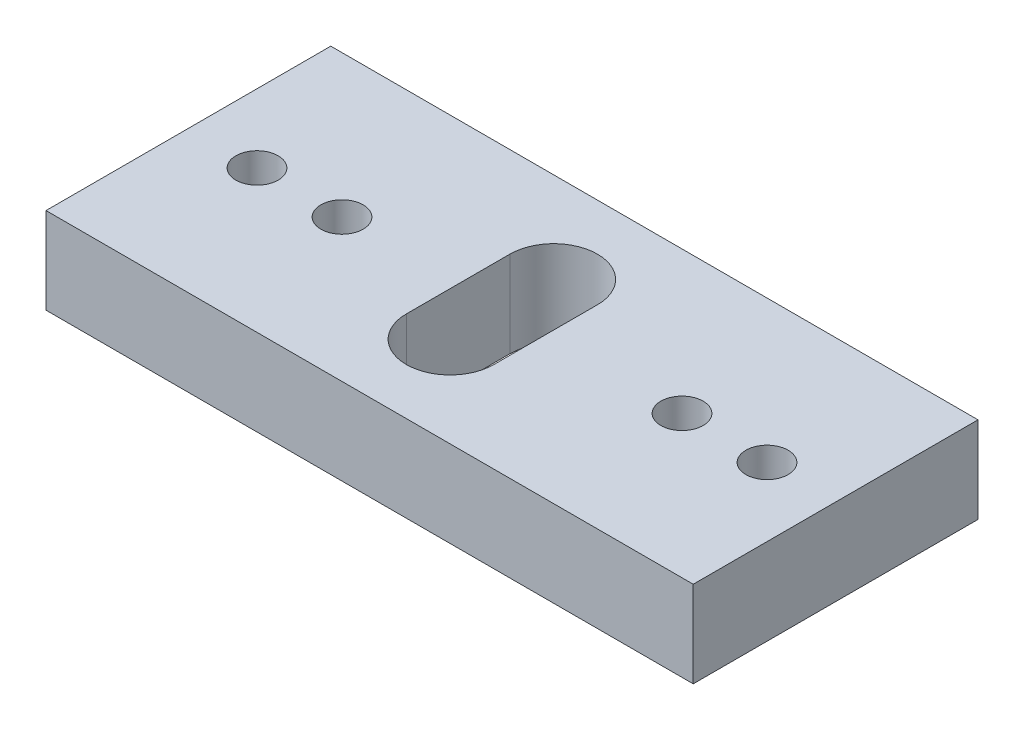
SolidWorks part; units mm, degrees
ref_plane "Front Plane" through (0, 0, 0) normal (0, 0, 1) x (1, 0, 0)
ref_plane "Top Plane" through (0, 0, 0) normal (0, 1, 0) x (1, 0, 0)
ref_plane "Right Plane" through (0, 0, 0) normal (1, 0, 0) x (0, 0, -1)
sketch "Sketch1" plane through (0, 0, 0) normal (0, 1, 0) x (1, 0, 0)
  line L0 (0, 0) -> (0, 10.1312) construction
  line L1 (0, 0) -> (-39.2364, 0) construction
  line L2 (19.05, 8.382) -> (-19.05, 8.382)
  line L3 (-19.05, 8.382) -> (-19.05, -8.382)
  line L4 (0, 0) -> (0, -10.5582) construction
  line L5 (19.05, 8.382) -> (19.05, -8.382)
  line L6 (19.05, -8.382) -> (-19.05, -8.382)
  line L9 (1.9844, -3.048) -> (1.9844, 3.048)
  line L11 (-3.175, -3.048) -> (-3.175, 3.048)
  arc A0 (1.9844, 3.048) -> (-3.175, 3.048) centre (-0.5953, 3.048) ccw
  circle A1 centre (-10.0076, 0) radius 1.2446
  circle A2 centre (-15.0114, 0) radius 1.2446
  arc A3 (1.9844, -3.048) -> (-3.175, -3.048) centre (-0.5953, -3.048) cw
  circle A13 centre (15.0114, 0) radius 1.2446
  circle A14 centre (10.0076, 0) radius 1.2446
  point P14 (0, 8.382)
  point P16 (-19.05, 0)
  point P17 (19.05, 0)
  point P20 (1.9844, 0)
  point P24 (-3.175, 0)
  dimension "D1" = 3.048
  dimension "D2" = 2.4892
  dimension "D5" = 2.4892
  dimension "D7" = 8.382
  dimension "D10" = 3.175
  dimension "D11" = 2.5797
  dimension "D3" = 10.0076
  dimension "D4" = 5.0038
  dimension "D6" = 19.05
  dimension "D8" = 5.1594
  dimension "D9" = 6.096
extrude "Boss-Extrude1" add sketch "Sketch1" along normal blind 5.08
